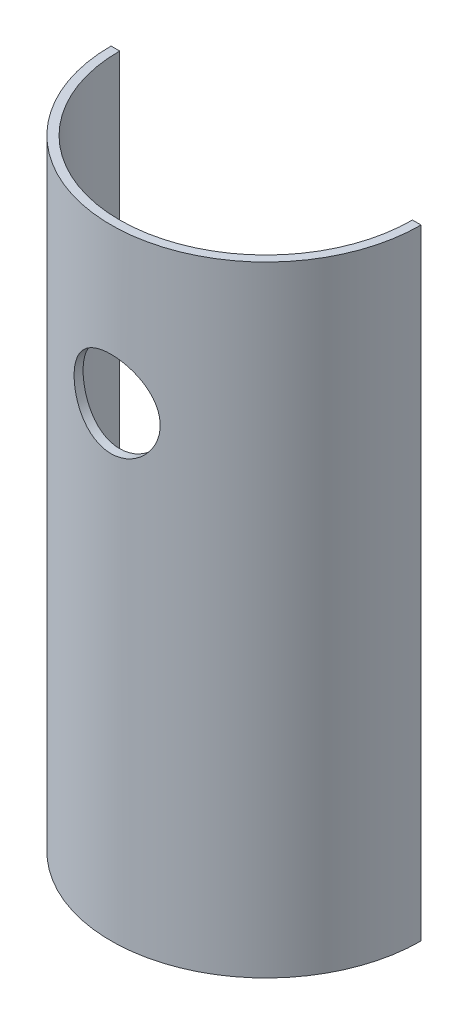
SolidWorks part; units mm, degrees
ref_plane "Front Plane" through (0, 0, 0) normal (0, 0, 1) x (1, 0, 0)
ref_plane "Top Plane" through (0, 0, 0) normal (0, 1, 0) x (1, 0, 0)
ref_plane "Right Plane" through (0, 0, 0) normal (1, 0, 0) x (0, 0, -1)
sketch "Sketch1" plane through (0, 0, 0) normal (0, 1, 0) x (1, 0, 0)
  line L0 (-45, 0) -> (-42.5, 0)
  line L1 (42.5, 0) -> (45, 0)
  arc A0 (-45, 0) -> (45, 0) centre (0, 0) ccw
  arc A1 (-42.5, 0) -> (42.5, 0) centre (0, 0) ccw
  dimension "D1" = 90
  dimension "D2" = 85
extrude "Boss-Extrude1" add sketch "Sketch1" along normal blind 180
sketch "Sketch2" plane through (0, 0, 0) normal (0, 0, 1) x (1, 0, 0)
  line L0 (45, 180) -> (-45, 180) construction
  circle A0 centre (0, 135) radius 12.5
  dimension "D1" = 25
  dimension "D2" = 45
extrude "Cut-Extrude1" cut sketch "Sketch2" along normal through all
